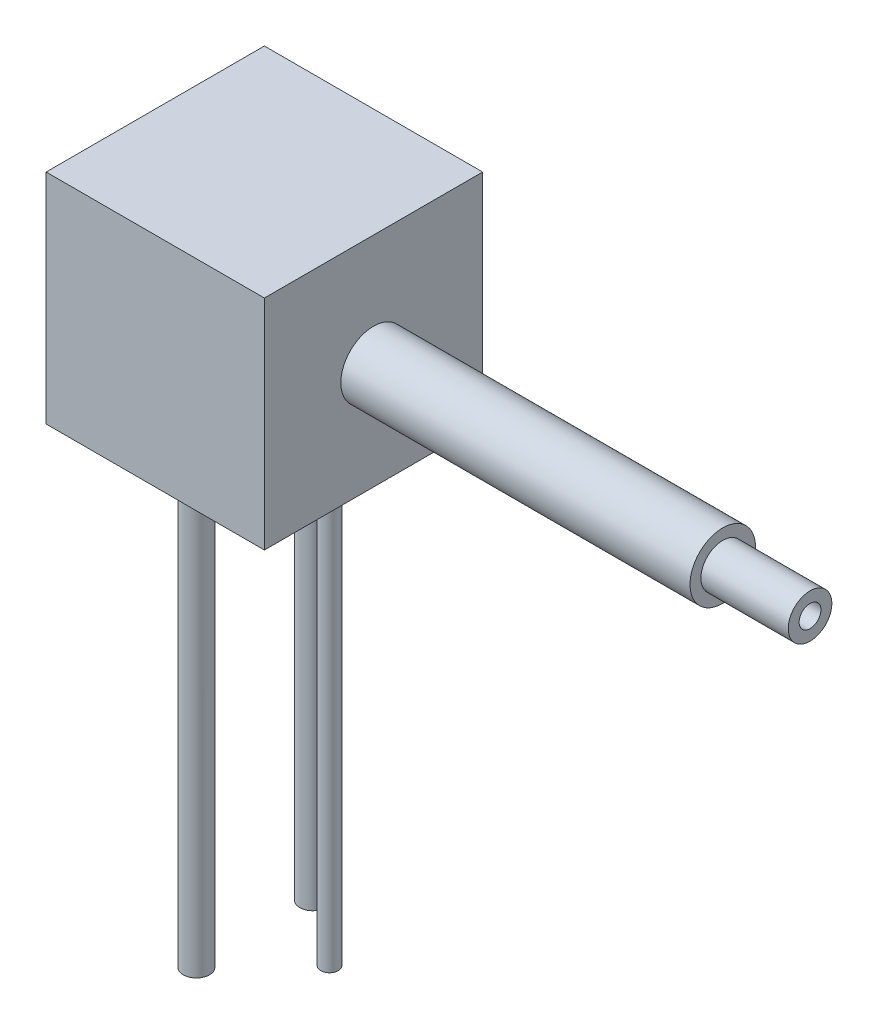
SolidWorks part; units mm, degrees
ref_plane "Front Plane" through (0, 0, 0) normal (0, 0, 1) x (1, 0, 0)
ref_plane "Top Plane" through (0, 0, 0) normal (0, 1, 0) x (1, 0, 0)
ref_plane "Right Plane" through (0, 0, 0) normal (1, 0, 0) x (0, 0, -1)
sketch "Sketch1" plane through (0, 0, 0) normal (0, 1, 0) x (1, 0, 0)
  line L1 (-250, 250) -> (250, 250)
  line L2 (-250, 250) -> (-250, -250)
  line L3 (-250, -250) -> (250, -250)
  line L4 (250, 250) -> (250, -250)
  line L5 (-250, 250) -> (250, -250) construction
  line L6 (-250, -250) -> (250, 250) construction
  point P0 (0, 0)
  dimension "D1" = 500
  dimension "D2" = 500
extrude "Boss-Extrude1" add sketch "Sketch1" along normal blind 500
sketch "Sketch2" plane through (0, 0, 0) normal (0, -1, 0) x (1, 0, 0)
  circle A0 centre (0, 155.7539) radius 30
  circle A1 centre (-149.2212, 0) radius 20
  circle A2 centre (149.2212, 0) radius 20
  circle A3 centre (0, -111.0563) radius 30
  dimension "D1" = 60
  dimension "D2" = 40
  dimension "D3" = 40
  dimension "D4" = 60
extrude "Boss-Extrude2" add sketch "Sketch2" along normal blind 1000
sketch "Sketch3" plane through (250, 0, 0) normal (1, 0, 0) x (0, 0, -1)
  circle A0 centre (0, 244.0803) radius 75
  dimension "D1" = 150
extrude "Boss-Extrude3" add sketch "Sketch3" along normal blind 800
sketch "Sketch4" plane through (1050, 0, 0) normal (1, 0, 0) x (0, 0, -1)
  circle A0 centre (0, 244.0803) radius 50
  dimension "D1" = 100
extrude "Boss-Extrude4" add sketch "Sketch4" along normal blind 200
sketch "Sketch5" plane through (1250, 0, 0) normal (1, 0, 0) x (0, 0, -1)
  circle A0 centre (0, 244.0803) radius 25
  dimension "D1" = 50
extrude "Cut-Extrude1" cut sketch "Sketch5" against normal blind 1200
sketch "Sketch6" plane through (0, -1000, 0) normal (0, -1, 0) x (1, 0, 0)
  circle A0 centre (0, 155.7539) radius 15
  circle A1 centre (149.2212, 0) radius 10
  circle A2 centre (0, -111.0563) radius 15
  circle A3 centre (-149.2212, 0) radius 10
  dimension "D1" = 30
  dimension "D2" = 30
  dimension "D3" = 20
  dimension "D4" = 20
extrude "Cut-Extrude2" cut sketch "Sketch6" against normal blind 200
